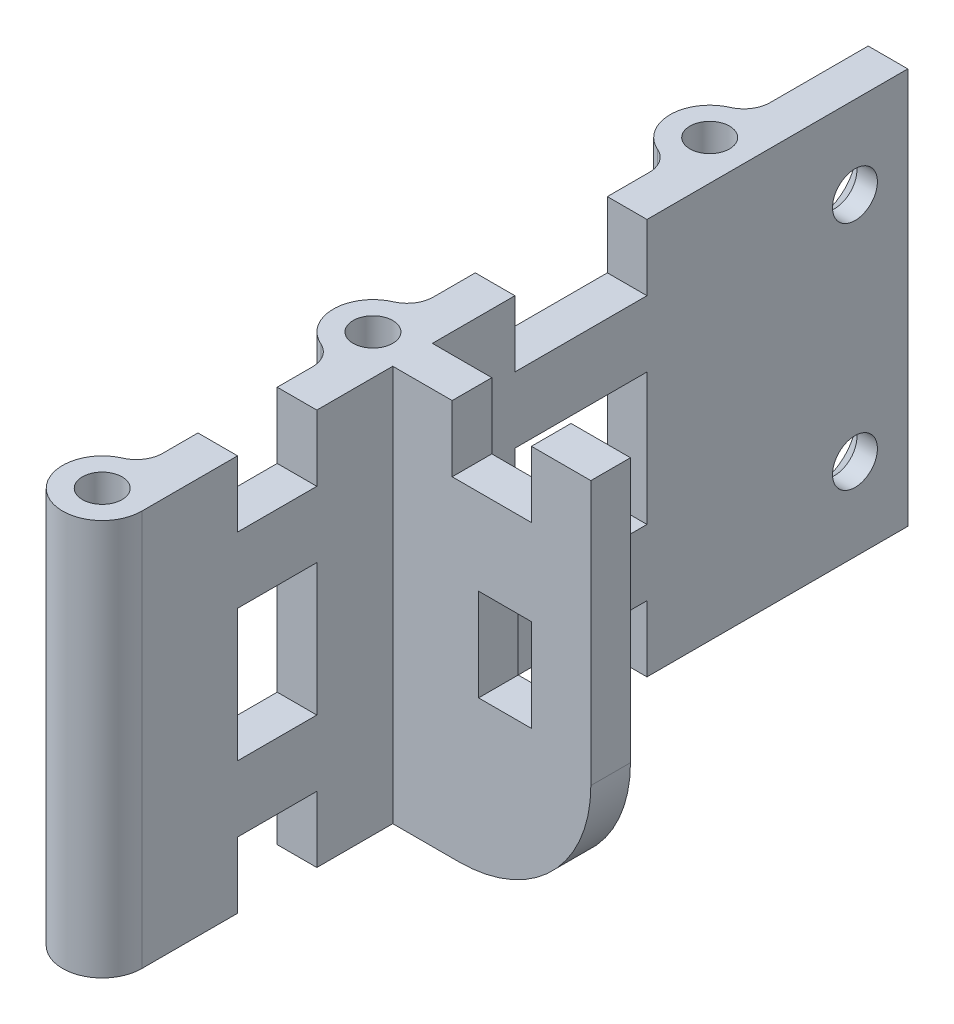
SolidWorks part; units mm, degrees
ref_plane "Front Plane" through (0, 0, 0) normal (0, 0, 1) x (1, 0, 0)
ref_plane "Top Plane" through (0, 0, 0) normal (0, 1, 0) x (1, 0, 0)
ref_plane "Right Plane" through (0, 0, 0) normal (1, 0, 0) x (0, 0, -1)
sketch "Sketch1" plane through (0, 0, 0) normal (0, 1, 0) x (1, 0, 0)
  line L0 (0, -58) -> (0, 0)
  line L1 (0, 0) -> (3, 0)
  line L2 (3, 0) -> (3, -36)
  line L3 (3, -36) -> (18, -36)
  line L4 (18, -36) -> (18, -39)
  line L5 (18, -39) -> (3, -39)
  line L6 (3, -39) -> (3, -58)
  line L7 (3, -58) -> (0, -58)
  line L9 (3, -35.5) -> (23.8, -35.5) construction
  dimension "D1" = 3
  dimension "D2" = 58
  dimension "D3" = 15
  dimension "D4" = 0.5
extrude "Boss-Extrude1" add sketch "Sketch1" along normal blind 30
hole_wizard "CSK for M3 Countersunk Flat Head Screw1" positions "Sketch3" profile "Sketch2" countersink size "M3" standard "ISO" end condition through all
sketch "Sketch3" plane through (0, 0, 0) normal (-1, 0, 0) x (0, 0, 1)
  line L0 (0, 15) -> (-50000, 15) construction
  line L1 (58, 30) -> (58, 0) construction
  line L2 (4, 21.2222) -> (4, -49978.7778) construction
  line L3 (0, 30) -> (0, 0) construction
  point P0 (4, 23.75)
  point P2 (4, 6.25)
  point P7 (58, 15)
  dimension "D1" = 17.5
  dimension "D2" = 4
sketch "Sketch2" plane through (0, 23.75, 4) normal (0, 1, 0) x (0, 0, 1)
  line L0 (0, 0) -> (0, 18)
  line L1 (0, 18) -> (1.7, 18)
  line L2 (1.7, 18) -> (1.7, 1.45)
  line L3 (1.7, 1.45) -> (3.15, 0)
  line L5 (3.15, 0) -> (0, 0)
  line L6 (-1.7, 1.45) -> (-3.15, 0) construction
  line L11 (0, -6.35) -> (0, 107.95) construction
  dimension "Thru Hole Dia." = 3.4
  dimension "Thru Hole Depth" = 18
  dimension "Near C'Sink Dia." = 6.3
  dimension "Near C'Sink Angle" = 90
sketch "Sketch4" plane through (0, 0, 0) normal (0, 1, 0) x (1, 0, 0)
  line L0 (0, 0) -> (0, -58) construction
  line L1 (18, -37.5) -> (-49982, -37.5) construction
  line L2 (18, -39) -> (18, -36) construction
  circle A0 centre (0, -12) radius 3
  circle A1 centre (0, -37.5) radius 3
  circle A2 centre (0, -58) radius 3
  point P14 (18, -37.5)
  dimension "D1" = 12
extrude "Boss-Extrude2" add sketch "Sketch4" along normal up to surface (30 mm away) up to face at (6, 30, 33.25)
sketch "Sketch5" plane through (0, 30, 0) normal (0, 1, 0) x (1, 0, 0)
  circle A0 centre (0, -12) radius 1.5
  circle A1 centre (0, -37.5) radius 1.5
  circle A2 centre (0, -58) radius 1.5
  dimension "D1" = 3
extrude "Cut-Extrude1" cut sketch "Sketch5" against normal through all
sketch "Sketch7" plane through (0, 0, 36) normal (0, 0, -1) x (-1, 0, 0)
  line L0 (-13, 18) -> (-10, 18) construction
  line L1 (-13.5, 18.5) -> (-9.5, 18.5)
  line L2 (-13.5, 18.5) -> (-13.5, 11.5)
  line L3 (-13.5, 11.5) -> (-9.5, 11.5)
  line L4 (-9.5, 18.5) -> (-9.5, 11.5)
  line L5 (-10, 12) -> (-13, 12) construction
  line L6 (-10, 18) -> (-10, 12) construction
  line L7 (-13, 12) -> (-13, 18) construction
  dimension "D1" = 0.5
  dimension "D2" = 0.5
  dimension "D3" = 0.5
  dimension "D4" = 0.5
extrude "Cut-Extrude2" cut sketch "Sketch7" against normal up to next
sketch "Sketch10" plane through (0, 0, 0) normal (-1, 0, 0) x (0, 0, 1)
  line L0 (24.75, 0) -> (24.75, 50000) construction
  line L1 (15, 0) -> (34.5, 0) construction
  line L2 (47.75, 0) -> (47.75, 50000) construction
  line L3 (40.5, 0) -> (55, 0) construction
  line L4 (15, 30) -> (34.5, 30) construction
  line L5 (19.75, 30) -> (29.75, 30)
  line L6 (19.75, 30) -> (19.75, 25)
  line L7 (19.75, 25) -> (29.75, 25)
  line L8 (29.75, 30) -> (29.75, 25)
  line L9 (40.5, 30) -> (55, 30) construction
  line L10 (44.75, 30) -> (50.75, 30)
  line L11 (44.75, 30) -> (44.75, 25)
  line L12 (44.75, 25) -> (50.75, 25)
  line L13 (50.75, 30) -> (50.75, 25)
  line L14 (15, 15) -> (50015, 15) construction
  line L15 (19.75, 0) -> (29.75, 0)
  line L16 (19.75, 0) -> (19.75, 5)
  line L17 (19.75, 5) -> (29.75, 5)
  line L18 (29.75, 0) -> (29.75, 5)
  line L19 (44.75, 0) -> (50.75, 0)
  line L20 (44.75, 0) -> (44.75, 5)
  line L21 (44.75, 5) -> (50.75, 5)
  line L22 (50.75, 0) -> (50.75, 5)
  line L23 (19.75, 20) -> (29.75, 20)
  line L24 (19.75, 20) -> (19.75, 10)
  line L25 (19.75, 10) -> (29.75, 10)
  line L26 (29.75, 20) -> (29.75, 10)
  line L27 (15, 0) -> (15, 30) construction
  line L29 (44.75, 20) -> (50.75, 20)
  line L30 (44.75, 20) -> (44.75, 10)
  line L31 (44.75, 10) -> (50.75, 10)
  line L32 (50.75, 20) -> (50.75, 10)
  point P4 (24.75, 0)
  point P9 (47.75, 0)
  point P38 (15, 15)
  dimension "D1" = 10
  dimension "D2" = 6
  dimension "D3" = 5
  dimension "D4" = 5
extrude "Cut-Extrude3" cut sketch "Sketch10" against normal up to next
sketch "Sketch11" plane through (0, 0, 39) normal (0, 0, 1) x (1, 0, 0)
  line L0 (3, 30) -> (18, 30) construction
  line L1 (7.5, 30) -> (13.5, 30)
  line L2 (7.5, 30) -> (7.5, 25)
  line L3 (7.5, 25) -> (13.5, 25)
  line L4 (13.5, 30) -> (13.5, 25)
  line L10 (3, 25) -> (3, 30) construction
  line L11 (3, 30) -> (3, 0) construction
  dimension "D1" = 4.5
  dimension "D2" = 6
extrude "Cut-Extrude4" cut sketch "Sketch11" against normal up to next
fillet "Fillet1" radius 2 5 edges at (0, 15, 55) (0, 15, 40.5) (0, 15, 34.5) (0, 15, 15) (0, 15, 9)
fillet "Fillet2" radius 10 1 edges at (18, 0, 37.5)
